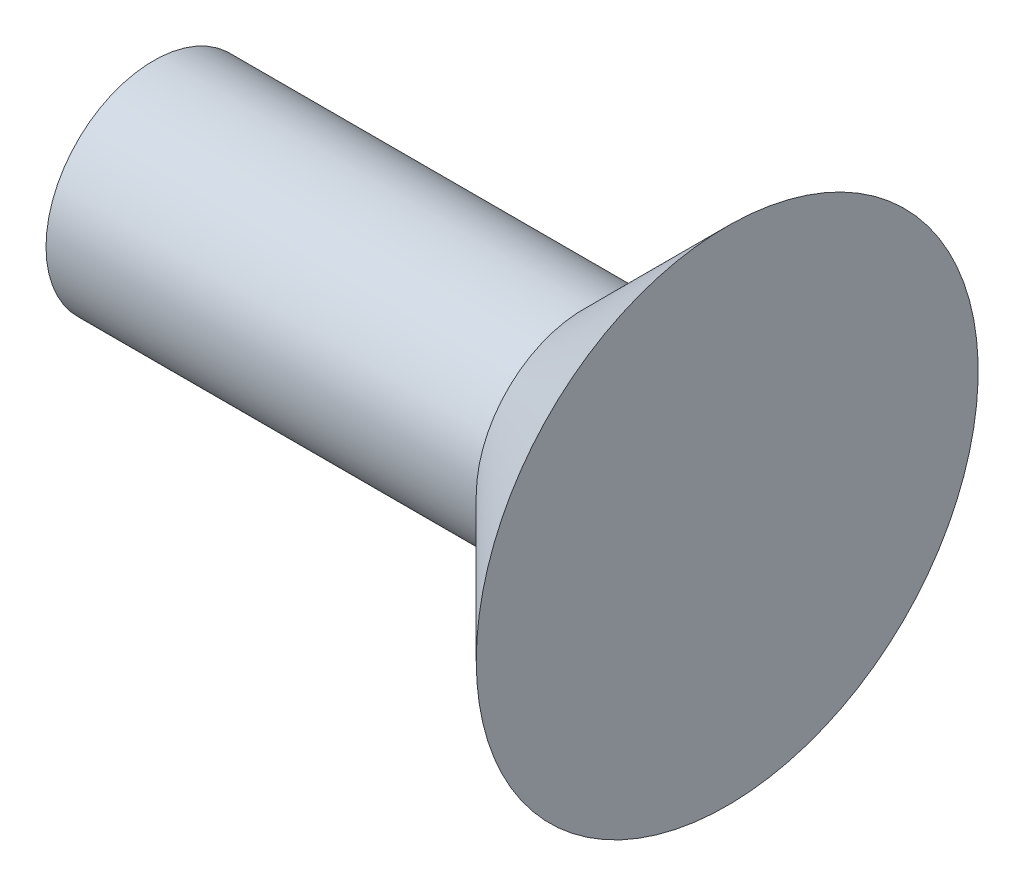
SolidWorks part; units mm, degrees
ref_plane "Front Plane" through (0, 0, 0) normal (0, 0, 1) x (1, 0, 0)
ref_plane "Top Plane" through (0, 0, 0) normal (0, 1, 0) x (1, 0, 0)
ref_plane "Right Plane" through (0, 0, 0) normal (1, 0, 0) x (0, 0, -1)
sketch "Sketch1" plane through (0, 0, 0) normal (0, 0, 1) x (1, 0, 0)
  line L0 (-84.0032, 19.2344) -> (-72.0032, 19.2344)
  line L1 (-70.0032, 17.7344) -> (-70.0032, 21.2344)
  line L2 (-84.0032, 19.2344) -> (-84.0032, 17.7344)
  line L3 (-72.0032, 19.2344) -> (-70.0032, 21.2344)
  line L4 (-84.0032, 17.7344) -> (-70.0032, 17.7344) construction
  line L5 (-70.0032, 17.7344) -> (-84.0032, 17.7344)
revolve "Revolve2" add sketch "Sketch1" angle 360 about L4
sketch "Sketch2" plane through (-84.0032, 0, 0) normal (-1, 0, 0) x (0, 0, 1)
  line L0 (-1.9611, 19.6488) -> (-2.0812, 15.9401)
  line L1 (-2.0812, 15.9401) -> (2.1998, 15.8015)
  line L2 (2.1998, 15.8015) -> (2.0945, 19.7422)
  line L3 (2.0945, 19.7422) -> (-1.9611, 19.6488)
extrude "Cut-Extrude1" cut sketch "Sketch2" against normal blind 6
